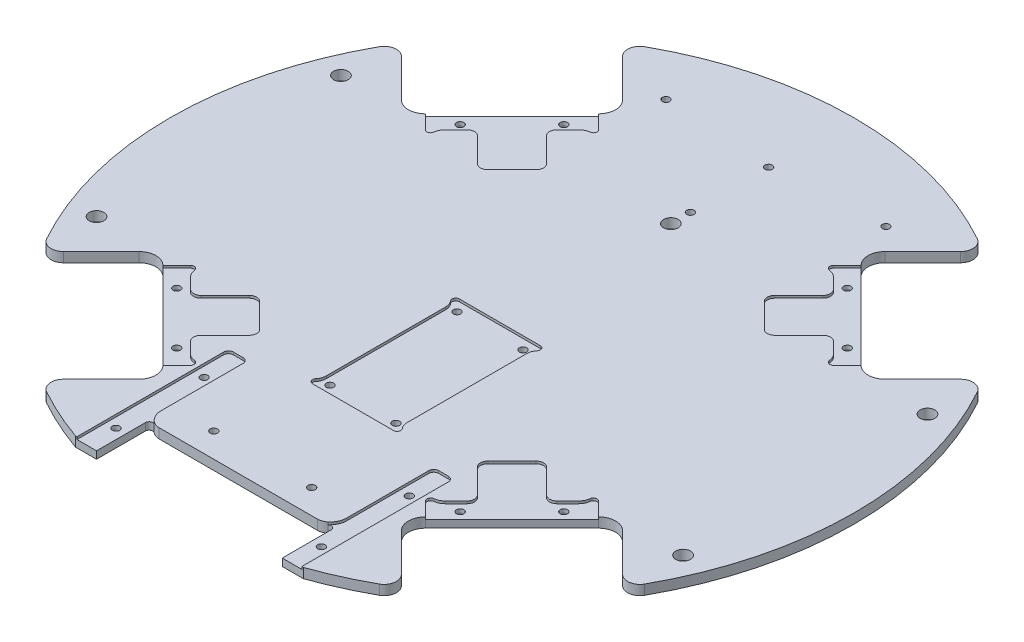
SolidWorks part; units mm, degrees
material "ABS PC"
ref_plane "Front Plane" through (0, 0, 0) normal (0, 0, 1) x (1, 0, 0)
ref_plane "Top Plane" through (0, 0, 0) normal (0, 1, 0) x (1, 0, 0)
ref_plane "Right Plane" through (0, 0, 0) normal (1, 0, 0) x (0, 0, -1)
sketch "Sketch1" plane through (0, 0, 0) normal (0, 1, 0) x (1, 0, 0)
  circle A0 centre (0, 0) radius 140
  dimension "D1" = 280
extrude "Boss-Extrude1" add sketch "Sketch1" along normal blind 4
sketch "Sketch7" plane through (0, 4, 0) normal (0, 1, 0) x (1, 0, 0)
  line L0 (-89.1308, -53.7048) -> (-53.7048, -89.1308)
  line L1 (-98.9596, -53.7048) -> (-121.6224, -76.3675)
  line L2 (-53.7048, -98.9596) -> (-76.3675, -121.6224)
  line L3 (-121.6224, -76.3675) -> (-76.3675, -121.6224)
  line L4 (0, 0) -> (-98.9949, -98.9949) construction
  line L7 (0, 0) -> (0, 130) construction
  circle A0 centre (0, 0) radius 140 construction
  arc A1 (-98.9596, -53.7048) -> (-89.1308, -53.7048) centre (-94.0452, -58.6192) cw
  arc A2 (-53.7048, -89.1308) -> (-53.7048, -98.9596) centre (-58.6192, -94.0452) cw
  dimension "D4" = 6.95
  dimension "D1" = 101
  dimension "D2" = 64
  dimension "D3" = 135
extrude "Cut-Extrude4" cut sketch "Sketch7" against normal up to next
sketch "Sketch8" plane through (0, 4, 0) normal (0, 1, 0) x (1, 0, 0)
  line L0 (-89.1308, -53.7048) -> (-53.7048, -89.1308)
  line L1 (-89.1308, -53.7048) -> (-83.474, -48.0479)
  line L2 (-53.7048, -89.1308) -> (-48.0479, -83.474)
  line L3 (-79.4765, -52.0454) -> (-52.0454, -79.4765)
  line L6 (-53.7048, -89.1308) -> (-89.1308, -53.7048) construction
  arc A0 (-83.474, -48.0479) -> (-80.9197, -48.9704) centre (-82.4133, -49.1086) cw
  arc A1 (-80.9197, -48.9704) -> (-79.4765, -52.0454) centre (-75.9409, -48.5099) ccw
  arc A2 (-48.0479, -83.474) -> (-48.9704, -80.9197) centre (-49.1086, -82.4133) ccw
  arc A3 (-48.9704, -80.9197) -> (-52.0454, -79.4765) centre (-48.5099, -75.9409) cw
  dimension "D2" = 1.5
  dimension "D3" = 5
  dimension "D4" = 1.5
  dimension "D5" = 5
  dimension "D1" = 8
extrude "Cut-Extrude5" cut sketch "Sketch8" against normal blind 1
sketch "Sketch14" plane through (0, 4, 0) normal (0, 1, 0) x (1, 0, 0)
  line L0 (-52.0454, -79.4765) -> (-79.4765, -52.0454) construction
  line L1 (-52.0454, -79.4765) -> (-79.4765, -52.0454) construction
  line L2 (-70.7107, -56.5685) -> (-60.8112, -46.669)
  line L3 (-56.5685, -70.7107) -> (-46.669, -60.8112)
  line L4 (-56.5685, -46.669) -> (-46.669, -56.5685)
  line L5 (-74.9533, -56.5685) -> (-56.5685, -74.9533)
  line L8 (-83.474, -48.0479) -> (-89.1308, -53.7048) construction
  arc A0 (-74.9533, -56.5685) -> (-70.7107, -56.5685) centre (-72.832, -54.4472) ccw
  arc A1 (-56.5685, -74.9533) -> (-56.5685, -70.7107) centre (-54.4472, -72.832) cw
  arc A2 (-60.8112, -46.669) -> (-56.5685, -46.669) centre (-58.6899, -48.7904) cw
  arc A3 (-46.669, -60.8112) -> (-46.669, -56.5685) centre (-48.7904, -58.6899) ccw
  dimension "D1" = 3
  dimension "D2" = 20
  dimension "D3" = 20
  dimension "D4" = 15.05
extrude "Cut-Extrude10" cut sketch "Sketch14" against normal up to surface (1 mm away) up to face at (-66.8825, 3, 66.8825)
sketch "Sketch9" plane through (0, 3, 0) normal (0, 1, 0) x (1, 0, 0)
  line L0 (-48.0479, -83.474) -> (-83.474, -48.0479) construction
  line L3 (-48.0479, -83.474) -> (-83.474, -48.0479) construction
  line L4 (-98.9596, -53.7048) -> (-119.0017, -73.7469) construction
  circle A0 centre (-79.196, -57.9828) radius 1.5
  circle A1 centre (-57.9828, -79.196) radius 1.5
  dimension "D4" = 3
  dimension "D1" = 4
  dimension "D2" = 30
  dimension "D3" = 17
  dimension "D5" = 4
extrude "Cut-Extrude6" cut sketch "Sketch9" against normal up to next
fillet "Fillet1" radius 5 2 edges at (-73.7469, 2, 119.0017) (-119.0017, 2, 73.7469)
pattern_circular "CirPattern1" count 4 over 360 about axis through (0, 0, 0) along (0, 1, 0) of "Cut-Extrude4", "Cut-Extrude6", "Fillet1", "Cut-Extrude5", "Cut-Extrude10"
sketch "Sketch2" plane through (0, 4, 0) normal (0, 1, 0) x (1, 0, 0)
  line L0 (-46.6476, -132) -> (-38, -132)
  line L1 (-38, -132) -> (-38, -112)
  line L2 (-32.3467, -112) -> (32.3467, -112)
  line L3 (38, -112) -> (38, -132)
  line L4 (38, -132) -> (46.6476, -132)
  line L5 (46.6476, -132) -> (46.6476, -140)
  line L6 (46.6476, -140) -> (-46.6476, -140)
  line L7 (-46.6476, -140) -> (-46.6476, -132)
  circle A0 centre (0, 0) radius 140 construction
  arc A1 (-38, -112) -> (-35.5415, -110.8462) centre (-36.5, -112) cw
  arc A2 (-32.3467, -112) -> (-35.5415, -110.8462) centre (-32.3467, -107) cw
  arc A3 (38, -112) -> (35.5415, -110.8462) centre (36.5, -112) ccw
  arc A4 (32.3467, -112) -> (35.5415, -110.8462) centre (32.3467, -107) ccw
  dimension "D5" = 1.5
  dimension "D6" = 5
  dimension "D1" = 8
  dimension "D2" = 20
  dimension "D3" = 76
  dimension "D4" = 8.6476
extrude "Cut-Extrude1" cut sketch "Sketch2" against normal up to next
sketch "Sketch3" plane through (0, 4, 0) normal (0, 1, 0) x (1, 0, 0)
  line L0 (-38, -132) -> (-46.6476, -132) construction
  line L1 (-38, -132) -> (-46, -132)
  line L2 (-38, -132) -> (-38, -72)
  line L3 (-40, -70) -> (-44, -70)
  line L4 (-46, -132) -> (-46, -72)
  line L5 (38, -132) -> (46, -132)
  line L6 (38, -132) -> (38, -72)
  line L7 (40, -70) -> (44, -70)
  line L8 (46, -132) -> (46, -72)
  line L12 (-38, -112) -> (-38, -132) construction
  line L13 (38, -132) -> (38, -112) construction
  arc A0 (38, -72) -> (40, -70) centre (40, -72) cw
  arc A1 (44, -70) -> (46, -72) centre (44, -72) cw
  arc A2 (-38, -72) -> (-40, -70) centre (-40, -72) ccw
  arc A3 (-44, -70) -> (-46, -72) centre (-44, -72) ccw
  dimension "D5" = 2
  dimension "D1" = 8
  dimension "D2" = 62
extrude "Cut-Extrude2" cut sketch "Sketch3" against normal blind 1
sketch "Sketch18" plane through (0, 4, 0) normal (0, 1, 0) x (1, 0, 0)
  line L0 (-38, -112) -> (-38, -72) construction
  line L1 (-38, -112) -> (-38, -72) construction
  line L3 (-38, -105.608) -> (-38, -112)
  line L4 (-38, -112) -> (-35.5415, -110.8462)
  line L5 (38, -72) -> (38, -112) construction
  line L6 (38, -105.608) -> (38, -112)
  line L7 (38, -112) -> (35.5415, -110.8462)
  arc A0 (-35.5415, -110.8462) -> (-38, -105.608) centre (-31.1904, -105.608) cw
  arc A2 (-35.5415, -110.8462) -> (-32.3467, -112) centre (-32.3467, -107) ccw construction
  arc A3 (35.5415, -110.8462) -> (38, -105.608) centre (31.1904, -105.608) ccw
  arc A4 (32.3467, -112) -> (35.5415, -110.8462) centre (32.3467, -107) ccw construction
extrude "Cut-Extrude14" cut sketch "Sketch18" against normal up to surface (1 mm away) up to face at (41.4286, 3, 94.1674)
fillet "Fillet3" radius 1.5 8 edges at (57.9828, 0, 80.696) (79.196, 0, 59.4828) (79.196, 0, -56.4828) (57.9828, 0, -77.696) (-57.9828, 0, -77.696) (-79.196, 0, -56.4828) (-57.9828, 0, 80.696) (-79.196, 0, 59.4828)
sketch "Sketch10" plane through (0, 4, 0) normal (0, 1, 0) x (1, 0, 0)
  circle A0 centre (-13.5, -61) radius 1.5
  circle A1 centre (13.5, -61) radius 1.5
  circle A2 centre (-13.5, -9) radius 1.5
  circle A3 centre (13.5, -9) radius 1.5
  dimension "D3" = 3
  dimension "D1" = 13.5
  dimension "D2" = 27
  dimension "D4" = 61
  dimension "D5" = 52
extrude "Cut-Extrude7" cut sketch "Sketch10" against normal up to next
sketch "Sketch11" plane through (0, 4, 0) normal (0, 1, 0) x (1, 0, 0)
  line L0 (32.3467, -112) -> (-32.3467, -112) construction
  circle A0 centre (-20, -102) radius 1.5
  circle A1 centre (20, -102) radius 1.5
  dimension "D1" = 3
  dimension "D2" = 40
  dimension "D3" = 10
  dimension "D4" = 20
extrude "Cut-Extrude8" cut sketch "Sketch11" against normal up to next
sketch "Sketch13" plane through (0, 4, 0) normal (0, 1, 0) x (1, 0, 0)
  line L0 (-46, -132) -> (-38, -132) construction
  line L4 (-38, -105.608) -> (-38, -72) construction
  line L5 (38, -72) -> (38, -105.608) construction
  circle A0 centre (-42, -84) radius 1.5
  circle A1 centre (-42, -120) radius 1.5
  circle A2 centre (42, -120) radius 1.5
  circle A3 centre (42, -84) radius 1.5
  dimension "D1" = 3
  dimension "D2" = 12
  dimension "D3" = 36
  dimension "D4" = 4
  dimension "D5" = 4
extrude "Cut-Extrude9" cut sketch "Sketch13" against normal up to next
sketch "Sketch15" plane through (0, 4, 0) normal (0, 1, 0) x (1, 0, 0)
  line L1 (-16.55, -4.95) -> (16.55, -4.95)
  line L2 (-16.55, -10.6033) -> (-16.55, -59.3967)
  line L3 (-16.55, -65.05) -> (16.55, -65.05)
  line L4 (16.55, -10.6033) -> (16.55, -59.3967)
  circle A0 centre (-13.5, -61) radius 1.5 construction
  circle A1 centre (-13.5, -9) radius 1.5 construction
  arc A2 (-16.55, -4.95) -> (-17.7038, -7.4085) centre (-16.55, -6.45) ccw
  arc A3 (-16.55, -10.6033) -> (-17.7038, -7.4085) centre (-21.55, -10.6033) ccw
  arc A4 (16.55, -4.95) -> (17.7038, -7.4085) centre (16.55, -6.45) cw
  arc A5 (17.7038, -7.4085) -> (16.55, -10.6033) centre (21.55, -10.6033) ccw
  arc A6 (-16.55, -65.05) -> (-17.7038, -62.5915) centre (-16.55, -63.55) cw
  arc A7 (-17.7038, -62.5915) -> (-16.55, -59.3967) centre (-21.55, -59.3967) ccw
  arc A8 (16.55, -65.05) -> (17.7038, -62.5915) centre (16.55, -63.55) ccw
  arc A9 (17.7038, -62.5915) -> (16.55, -59.3967) centre (21.55, -59.3967) cw
  dimension "D3" = 4.05
  dimension "D5" = 1.5
  dimension "D6" = 5
  dimension "D1" = 33.1
  dimension "D2" = 4.05
  dimension "D4" = 16.55
extrude "Cut-Extrude11" cut sketch "Sketch15" against normal blind 1
sketch "Sketch16" plane through (0, 4, 0) normal (0, 1, 0) x (1, 0, 0)
  circle A0 centre (0, 73) radius 1.5
  circle A1 centre (-45, 108) radius 1.5
  circle A2 centre (45, 108) radius 1.5
  circle A3 centre (0, 105) radius 1.5
  circle A4 centre (0, 65) radius 3
  dimension "D2" = 3
  dimension "D5" = 6
  dimension "D1" = 73
  dimension "D3" = 108
  dimension "D4" = 90
  dimension "D6" = 32
  dimension "D7" = 65
extrude "Cut-Extrude12" cut sketch "Sketch16" against normal up to next
sketch "Sketch17" plane through (0, 4, 0) normal (0, 1, 0) x (1, 0, 0)
  circle A0 centre (-120, 50) radius 3
  circle A1 centre (-120, -50) radius 3
  circle A2 centre (120, 50) radius 3
  circle A3 centre (120, -50) radius 3
  dimension "D1" = 6
  dimension "D2" = 50
  dimension "D3" = 50
  dimension "D4" = 120
  dimension "D5" = 120
extrude "Cut-Extrude13" cut sketch "Sketch17" against normal up to next
